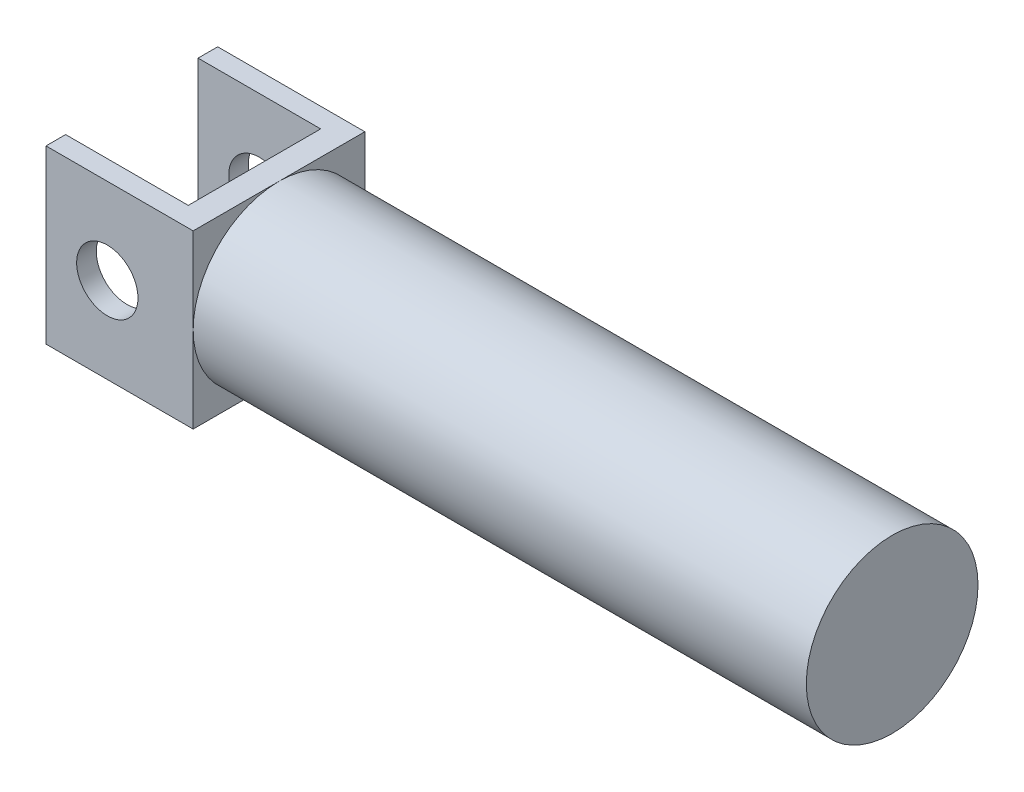
SolidWorks part; units mm, degrees
ref_plane "Front Plane" through (0, 0, 0) normal (1, 0, 0) x (0, 1, 0)
ref_plane "Top Plane" through (0, 0, 0) normal (0, 0, 1) x (0, 1, 0)
ref_plane "Right Plane" through (0, 0, 0) normal (0, 1, 0) x (-1, 0, 0)
sketch "Sketch2" plane through (0, 0, 0) normal (1, 0, 0) x (0, 1, 0)
  line L1 (-8.89, 8.89) -> (8.89, 8.89)
  line L2 (-8.89, 8.89) -> (-8.89, -8.89)
  line L3 (-8.89, -8.89) -> (8.89, -8.89)
  line L4 (8.89, 8.89) -> (8.89, -8.89)
  line L5 (-8.89, 8.89) -> (8.89, -8.89) construction
  line L6 (-8.89, -8.89) -> (8.89, 8.89) construction
  point P0 (0, 0)
  dimension "D1" = 17.78
  dimension "D2" = 17.78
extrude "Boss-Extrude1" add sketch "Sketch2" along normal blind 2.54
sketch "Sketch3" plane through (2.54, 0, 0) normal (1, 0, 0) x (0, 0, -1)
  circle A0 centre (0, 0) radius 8.89
  dimension "D1" = 17.78
extrude "Boss-Extrude2" add sketch "Sketch3" along normal blind 63.5
sketch "Sketch4" plane through (0, 0, 0) normal (-1, 0, 0) x (0, -1, 0)
  line L0 (0, 0) -> (536.6762, 0) construction
  line L1 (8.89, 8.89) -> (8.89, -8.89) construction
  line L2 (-8.89, 8.89) -> (8.89, 8.89)
  line L3 (-8.89, 8.89) -> (-8.89, 6.858)
  line L4 (-8.89, 6.858) -> (8.89, 6.858)
  line L5 (8.89, 8.89) -> (8.89, 6.858)
  line L6 (-8.89, -6.858) -> (8.89, -6.858)
  line L7 (8.89, -8.89) -> (8.89, -6.858)
  line L8 (-8.89, -8.89) -> (8.89, -8.89)
  line L9 (-8.89, -8.89) -> (-8.89, -6.858)
  dimension "D1" = 6.858
extrude "Boss-Extrude3" add sketch "Sketch4" along normal blind 12.7
sketch "Sketch5" plane through (0, 0, 8.89) normal (0, 0, 1) x (1, 0, 0)
  line L0 (2.54, 0) -> (-6.35, 0) construction
  circle A0 centre (-6.35, 0) radius 3.175
  dimension "D2" = 6.35
  dimension "D1" = 8.89
extrude "Cut-Extrude1" cut sketch "Sketch5" against normal through all
